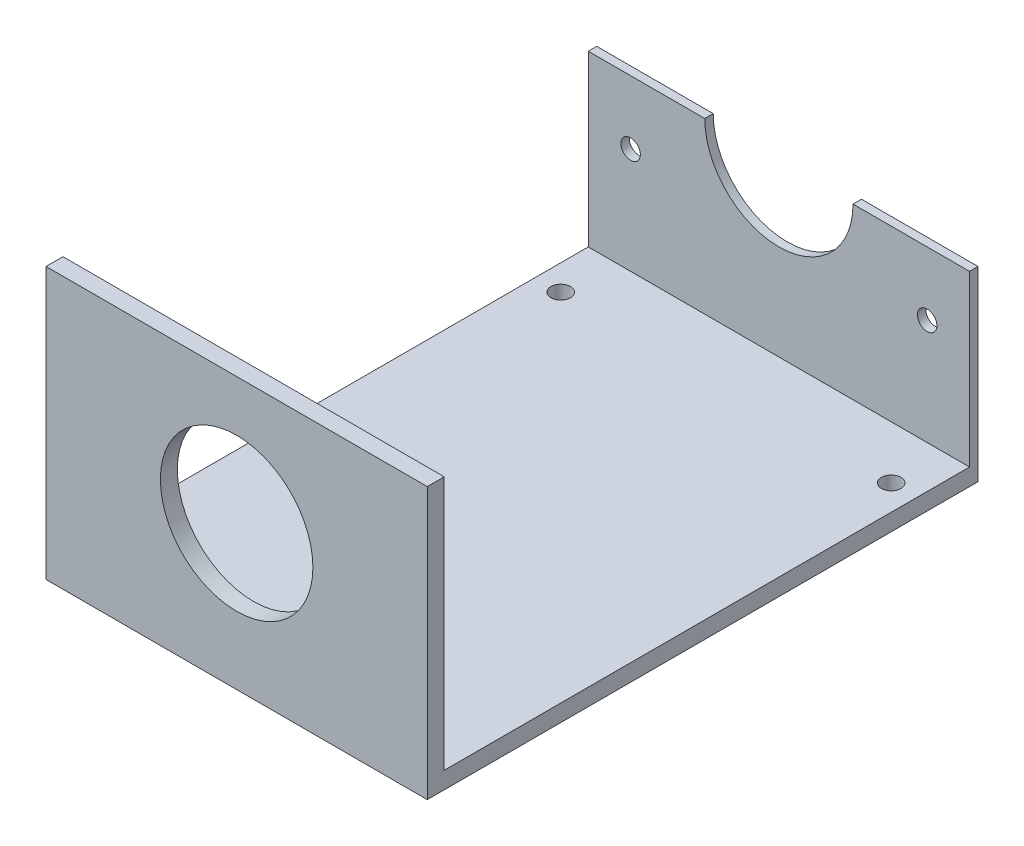
SolidWorks part; units mm, degrees
ref_plane "Front Plane" through (0, 0, 0) normal (0, 0, 1) x (1, 0, 0)
ref_plane "Top Plane" through (0, 0, 0) normal (0, 1, 0) x (1, 0, 0)
ref_plane "Right Plane" through (0, 0, 0) normal (1, 0, 0) x (0, 0, -1)
sketch "Sketch1" plane through (0, 0, 0) normal (0, 0, 1) x (1, 0, 0)
  line L1 (0, 0) -> (0, 40)
  line L3 (90, 40) -> (90, 0)
  line L4 (0, 40) -> (27.5, 40)
  line L5 (90, 40) -> (62.5, 40)
  line L8 (0, 0) -> (0, -4)
  line L9 (90, 0) -> (90, -4)
  line L10 (90, -4) -> (0, -4)
  arc A1 (62.5, 40) -> (27.5, 40) centre (45, 40) cw
  circle A2 centre (10, 25) radius 2.3
  circle A3 centre (80, 25) radius 2.3
extrude "Boss-Extrude1" add sketch "Sketch1" against normal blind 2
sketch "Sketch2" plane through (0, 0, 0) normal (0, 0, 1) x (1, 0, 0)
  line L0 (0, -4) -> (0, 0)
  line L1 (0, 0) -> (90, 0)
  line L2 (90, -4) -> (90, 40) construction
  line L3 (90, 0) -> (90, -4)
  line L4 (90, -4) -> (0, -4)
extrude "Boss-Extrude2" add sketch "Sketch2" along normal blind 128
sketch "Sketch3" plane through (0, 0, 0) normal (0, 1, 0) x (1, 0, 0)
  line L0 (0, -128) -> (0, -124)
  line L1 (0, -128) -> (0, 0) construction
  line L2 (0, -124) -> (90, -124)
  line L3 (90, -128) -> (90, 0) construction
  line L4 (90, -124) -> (90, -128)
  line L5 (90, -128) -> (0, -128)
extrude "Boss-Extrude3" add sketch "Sketch3" along normal blind 60
sketch "Sketch4" plane through (0, 0, 128) normal (0, 0, 1) x (1, 0, 0)
  circle A0 centre (45, 30) radius 18
extrude "Cut-Extrude1" cut sketch "Sketch4" against normal blind 60
sketch "Sketch5" plane through (0, 0, 0) normal (0, 1, 0) x (1, 0, 0)
  circle A0 centre (6, -12.5) radius 2.3
  circle A1 centre (84, -12.5) radius 2.3
extrude "Cut-Extrude2" cut sketch "Sketch5" against normal blind 60
